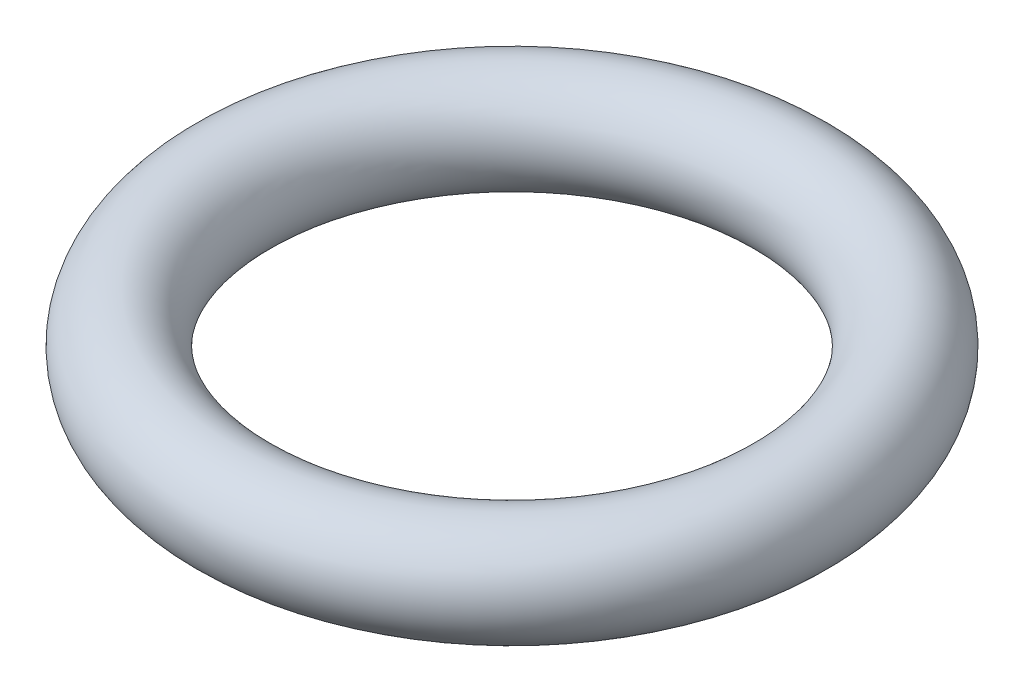
SolidWorks part; units mm, degrees
ref_plane "Front Plane" through (0, 0, 0) normal (0, 0, 1) x (1, 0, 0)
ref_plane "Top Plane" through (0, 0, 0) normal (0, 1, 0) x (1, 0, 0)
ref_plane "Right Plane" through (0, 0, 0) normal (1, 0, 0) x (0, 0, -1)
sketch "Sketch1" plane through (0, 0, 0) normal (0, 0, 1) x (1, 0, 0)
  line L0 (0, 0) -> (0, 8.6145) construction
  circle A0 centre (6.75, 0) radius 1.25
  point P5 (5.5, 0)
  point P6 (8, 0)
  dimension "D2" = 2.5
  dimension "D1" = 5.5
revolve "Revolve1" add sketch "Sketch1" angle 360 about L0
sketch "Sketch2" plane through (0, 0, 0) normal (0, 1, 0) x (1, 0, 0)
  circle A0 centre (0, 0) radius 6
  circle A1 centre (0, 0) radius 8
